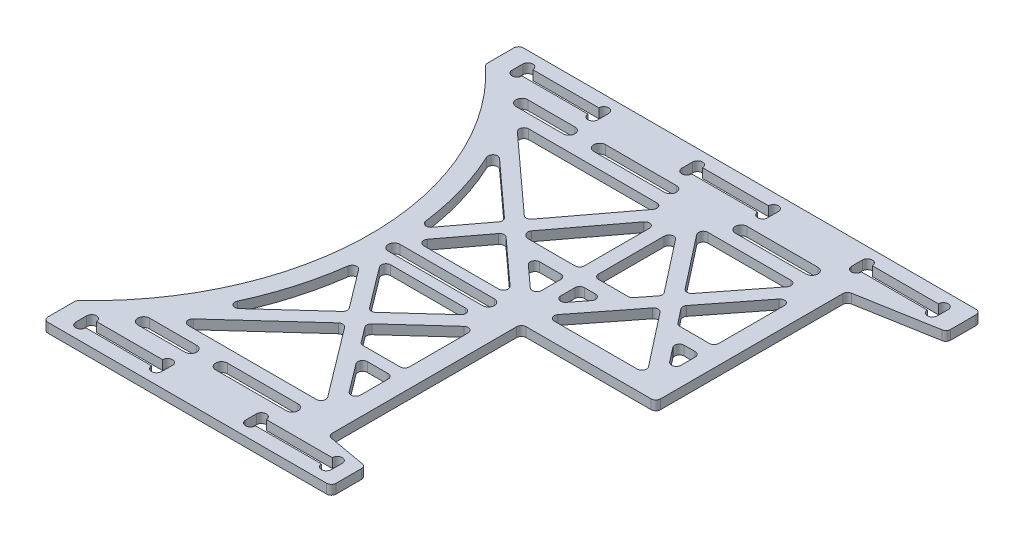
SolidWorks part; units mm, degrees
material "Thornel Mat VMA"
ref_plane "前视基准面" through (0, 0, 0) normal (0, 0, 1) x (1, 0, 0)
ref_plane "上视基准面" through (0, 0, 0) normal (0, 1, 0) x (1, 0, 0)
ref_plane "右视基准面" through (0, 0, 0) normal (1, 0, 0) x (0, 0, -1)
sketch "草图1" plane through (0, 0, 0) normal (0, 1, 0) x (1, 0, 0)
  line L0 (0, 0) -> (7.1511, 0) construction
  line L1 (-45.1, 47.4) -> (-26.9, 47.4)
  line L2 (-45.1, 47.4) -> (-45.1, 45.1)
  line L3 (-45.1, 45.1) -> (-26.9, 45.1)
  line L4 (-26.9, 47.4) -> (-26.9, 45.1)
  line L5 (-45.1, 47.4) -> (-26.9, 45.1) construction
  line L6 (-45.1, 45.1) -> (-26.9, 47.4) construction
  line L7 (9.1, 47.4) -> (-9.1, 47.4)
  line L8 (9.1, 47.4) -> (9.1, 45.1)
  line L9 (9.1, 45.1) -> (-9.1, 45.1)
  line L10 (-9.1, 47.4) -> (-9.1, 45.1)
  line L11 (9.1, 47.4) -> (-9.1, 45.1) construction
  line L12 (9.1, 45.1) -> (-9.1, 47.4) construction
  line L13 (45.1, 47.4) -> (26.9, 47.4)
  line L14 (45.1, 47.4) -> (45.1, 45.1)
  line L15 (45.1, 45.1) -> (26.9, 45.1)
  line L16 (26.9, 47.4) -> (26.9, 45.1)
  line L17 (45.1, 47.4) -> (26.9, 45.1) construction
  line L18 (45.1, 45.1) -> (26.9, 47.4) construction
  line L19 (0, 0) -> (0, 10.037) construction
  line L20 (45.1, -45.1) -> (26.9, -47.4) construction
  line L21 (49, -50.4) -> (-49, -50.4)
  line L22 (49, -50.4) -> (49, -43.1739)
  line L23 (49, 50.4) -> (-49, 50.4)
  line L24 (-49, -50.4) -> (-49, -43.3705)
  line L25 (49, -50.4) -> (-49, 50.4) construction
  line L26 (49, 50.4) -> (-49, -50.4) construction
  line L27 (45.1, -47.4) -> (26.9, -45.1) construction
  line L28 (9.1, -45.1) -> (-9.1, -47.4) construction
  line L29 (9.1, -47.4) -> (-9.1, -45.1) construction
  line L30 (-45.1, -45.1) -> (-26.9, -47.4) construction
  line L31 (-45.1, -47.4) -> (-26.9, -45.1) construction
  line L32 (26.9, -47.4) -> (26.9, -45.1)
  line L33 (45.1, -45.1) -> (26.9, -45.1)
  line L34 (45.1, -47.4) -> (45.1, -45.1)
  line L35 (45.1, -47.4) -> (26.9, -47.4)
  line L36 (-9.1, -47.4) -> (-9.1, -45.1)
  line L37 (9.1, -45.1) -> (-9.1, -45.1)
  line L38 (9.1, -47.4) -> (9.1, -45.1)
  line L39 (9.1, -47.4) -> (-9.1, -47.4)
  line L40 (-26.9, -47.4) -> (-26.9, -45.1)
  line L41 (-45.1, -45.1) -> (-26.9, -45.1)
  line L42 (-45.1, -47.4) -> (-45.1, -45.1)
  line L43 (-45.1, -47.4) -> (-26.9, -47.4)
  line L44 (-49, 43.3705) -> (-49, 50.4)
  line L45 (49, 43.1739) -> (31, 40)
  line L46 (31, 40) -> (31, -0.5)
  line L47 (31, -40) -> (49, -43.1739)
  line L48 (49, 43.1739) -> (49, 50.4)
  line L49 (-38, 40.1) -> (-28, 40.1) construction
  line L50 (-38, 41.35) -> (-28, 41.35)
  line L51 (-38, 38.85) -> (-28, 38.85)
  line L52 (-21.5, 40.1) -> (-6.5, 40.1) construction
  line L53 (-21.5, 41.35) -> (-6.5, 41.35)
  line L54 (-21.5, 38.85) -> (-6.5, 38.85)
  line L55 (8.5, 40.1) -> (23.5, 40.1) construction
  line L56 (8.5, 41.35) -> (23.5, 41.35)
  line L57 (8.5, 38.85) -> (23.5, 38.85)
  line L58 (31, -0.5) -> (2.5, -0.5)
  line L61 (-26.9, 46.25) -> (-9.1, 46.25) construction
  line L62 (-14, 46.25) -> (-14, 44.028) construction
  line L63 (-38, -40.1) -> (-28, -40.1) construction
  line L64 (-38, -41.35) -> (-28, -41.35)
  line L65 (-38, -38.85) -> (-28, -38.85)
  line L66 (-21.5, -40.1) -> (-6.5, -40.1) construction
  line L67 (-21.5, -41.35) -> (-6.5, -41.35)
  line L68 (-21.5, -38.85) -> (-6.5, -38.85)
  line L69 (2.5, -0.5) -> (2.5, -39.0048)
  line L72 (2.5, -39.0048) -> (31, -40)
  line L75 (-37.3687, 36.1) -> (-1.5, 36.1) construction
  line L76 (27, 36.1) -> (27, 3.5) construction
  line L77 (27, -36.1) -> (1.5, -36.1) construction
  line L78 (-26.0973, 3.5) -> (-1.5, 3.5) construction
  line L79 (-26.0973, -3.5) -> (-1.5, -3.5) construction
  line L80 (27, -3.5) -> (27, -36.1) construction
  line L81 (-1.5, 12.85) -> (-9.5573, 12.85)
  line L84 (1.5, 12.85) -> (6.9093, 12.85)
  line L87 (-1.5, 36.1) -> (-1.5, 3.5) construction
  line L88 (1.5, 36.1) -> (1.5, 3.5) construction
  line L89 (-25, 0) -> (-5, 0) construction
  line L90 (-25, 1.25) -> (-5, 1.25)
  line L91 (-25, -1.25) -> (-5, -1.25)
  line L92 (-12.8581, 15.85) -> (-1.5, 15.85)
  line L95 (9.2559, -23.75) -> (1.5, -23.75) construction
  line L98 (11.2114, -21.25) -> (1.5, -21.25) construction
  line L101 (-1.5, -3.5) -> (-1.5, -36.1) construction
  line L102 (1.5, -3.5) -> (27, -3.5) construction
  line L103 (1.5, -3.5) -> (1.5, -36.1) construction
  line L104 (1.5, 3.5) -> (27, 3.5) construction
  line L105 (-1.5, -36.1) -> (-37.3687, -36.1) construction
  line L106 (1.5, 36.1) -> (27, 36.1) construction
  line L107 (-26.0973, 3.5) -> (-1.5, 36.1) construction
  line L108 (-37.3687, 36.1) -> (-1.5, 3.5) construction
  line L109 (-35.1385, 36.1) -> (-16.2987, 18.977)
  line L110 (-34.3339, 31.3147) -> (-18.1131, 16.5722)
  line L111 (-26.2647, 5.7686) -> (-18.1131, 16.5722)
  line L112 (-24.2182, 3.5) -> (-15.8838, 14.546)
  line L113 (-35.1385, 36.1) -> (-3.3791, 36.1)
  line L114 (-1.5, 33.6096) -> (-1.5, 15.85)
  line L115 (-24.2182, 3.5) -> (-3.7302, 3.5)
  line L116 (-16.2987, 18.977) -> (-3.3791, 36.1)
  line L117 (-14.0693, 16.9508) -> (-12.8581, 15.85)
  line L118 (-14.0693, 16.9508) -> (-9.9102, 22.4631)
  line L119 (-15.8838, 14.546) -> (-3.7302, 3.5)
  line L120 (1.5, 5.9346) -> (6.9093, 12.85)
  line L121 (3.4044, 3.5) -> (14.25, 17.3654)
  line L122 (27, 36.1) -> (1.5, 3.5) construction
  line L123 (1.5, 36.1) -> (27, 3.5) construction
  line L124 (3.4044, 36.1) -> (14.25, 22.2346)
  line L125 (1.5, 33.6654) -> (8.2824, 24.9946)
  line L126 (3.4044, 36.1) -> (25.0956, 36.1)
  line L127 (27, 33.6654) -> (27, 15.85)
  line L128 (3.4044, 3.5) -> (25.0956, 3.5)
  line L129 (1.5, 5.9346) -> (1.5, 12.85)
  line L130 (14.25, 22.2346) -> (25.0956, 36.1)
  line L131 (16.1544, 19.8) -> (19.2441, 15.85)
  line L132 (16.1544, 19.8) -> (27, 33.6654)
  line L133 (14.25, 17.3654) -> (25.0956, 3.5)
  line L134 (3.4044, -3.5) -> (14.25, -17.3654) construction
  line L135 (14.25, -17.3654) -> (25.0956, -3.5) construction
  line L136 (3.4044, -3.5) -> (25.0956, -3.5) construction
  line L137 (16.1544, -19.8) -> (27, -33.6654) construction
  line L138 (16.1544, -19.8) -> (27, -5.9346) construction
  line L139 (27, -33.6654) -> (27, -5.9346) construction
  line L140 (3.4044, -36.1) -> (25.0956, -36.1) construction
  line L141 (14.25, -22.2346) -> (25.0956, -36.1) construction
  line L142 (3.4044, -36.1) -> (14.25, -22.2346) construction
  line L143 (1.5, -5.9346) -> (1.5, -21.25) construction
  line L144 (1.5, -5.9346) -> (12.3456, -19.8) construction
  line L145 (1.5, -33.6654) -> (9.2559, -23.75) construction
  line L147 (-14.0693, -16.9508) -> (-1.5, -5.527)
  line L148 (-1.5, -33.6096) -> (-1.5, -23.75)
  line L149 (-24.2182, -3.5) -> (-15.8838, -14.546)
  line L150 (-24.2182, -3.5) -> (-3.7302, -3.5)
  line L151 (-15.8838, -14.546) -> (-3.7302, -3.5)
  line L152 (-26.2647, -5.7686) -> (-18.1131, -16.5722)
  line L153 (-34.3339, -31.3147) -> (-18.1131, -16.5722)
  line L154 (-35.1385, -36.1) -> (-3.3791, -36.1)
  line L155 (-16.2987, -18.977) -> (-3.3791, -36.1)
  line L156 (-35.1385, -36.1) -> (-16.2987, -18.977)
  line L157 (-10.8255, -21.25) -> (-1.5, -21.25)
  line L160 (-8.9392, -23.75) -> (-1.5, -23.75)
  line L163 (14.25, -17.3654) -> (14.25, -10.4038) construction
  line L164 (-8.9392, -23.75) -> (-1.5, -33.6096)
  line L165 (11.2114, -21.25) -> (12.3456, -19.8) construction
  line L169 (1.5, -23.75) -> (1.5, -33.6654) construction
  line L170 (1.5, 15.85) -> (9.2559, 15.85)
  line L175 (-1.5, -21.25) -> (-1.5, -5.527)
  line L176 (-14.0693, -16.9508) -> (-10.8255, -21.25)
  line L178 (-1.5, 12.85) -> (-1.5, 5.527)
  line L181 (31, -31.8857) -> (31, -40) construction
  line L182 (9.2559, 15.85) -> (12.3456, 19.8)
  line L188 (-9.9102, 22.4631) -> (-1.5, 33.6096)
  line L189 (1.5, 15.85) -> (1.5, 33.6654)
  line L190 (8.2824, 24.9946) -> (12.3456, 19.8)
  line L191 (-9.5573, 12.85) -> (-1.5, 5.527)
  line L192 (19.2441, 15.85) -> (27, 15.85)
  line L193 (21.5907, 12.85) -> (27, 12.85)
  line L194 (21.5907, 12.85) -> (27, 5.9346)
  line L195 (27, 12.85) -> (27, 5.9346)
  line L196 (12.1, -39.34) -> (12.1, -50.4)
  line L197 (2.5, -39.0048) -> (2.5, -41.4811)
  line L198 (2.5, -41.4811) -> (12.1, -43.1739)
  circle A0 centre (-8.05, 47.4) radius 1.05
  circle A1 centre (8.05, 47.4) radius 1.05
  circle A2 centre (8.05, 45.1) radius 1.05
  circle A3 centre (-8.05, 45.1) radius 1.05
  circle A4 centre (-44.05, 47.4) radius 1.05
  circle A5 centre (-44.05, 45.1) radius 1.05
  circle A6 centre (-27.95, 47.4) radius 1.05
  circle A7 centre (-27.95, 45.1) radius 1.05
  circle A8 centre (27.95, 45.1) radius 1.05
  circle A9 centre (44.05, 45.1) radius 1.05
  circle A10 centre (44.05, 47.4) radius 1.05
  circle A11 centre (27.95, 47.4) radius 1.05
  circle A12 centre (27.95, -47.4) radius 1.05
  circle A13 centre (44.05, -47.4) radius 1.05
  circle A14 centre (44.05, -45.1) radius 1.05
  circle A15 centre (27.95, -45.1) radius 1.05
  circle A16 centre (-27.95, -45.1) radius 1.05
  circle A17 centre (-27.95, -47.4) radius 1.05
  circle A18 centre (-44.05, -45.1) radius 1.05
  circle A19 centre (-44.05, -47.4) radius 1.05
  circle A20 centre (-8.05, -45.1) radius 1.05
  circle A21 centre (8.05, -45.1) radius 1.05
  circle A22 centre (8.05, -47.4) radius 1.05
  circle A23 centre (-8.05, -47.4) radius 1.05
  arc A24 (-49, -43.3705) -> (-49, 43.3705) centre (-89, 0) ccw
  arc A25 (-38, 41.35) -> (-38, 38.85) centre (-38, 40.1) ccw
  arc A26 (-28, 38.85) -> (-28, 41.35) centre (-28, 40.1) ccw
  arc A27 (-21.5, 41.35) -> (-21.5, 38.85) centre (-21.5, 40.1) ccw
  arc A28 (-6.5, 38.85) -> (-6.5, 41.35) centre (-6.5, 40.1) ccw
  arc A29 (8.5, 41.35) -> (8.5, 38.85) centre (8.5, 40.1) ccw
  arc A30 (23.5, 38.85) -> (23.5, 41.35) centre (23.5, 40.1) ccw
  arc A33 (-38, -41.35) -> (-38, -38.85) centre (-38, -40.1) cw
  arc A34 (-28, -38.85) -> (-28, -41.35) centre (-28, -40.1) cw
  arc A35 (-21.5, -41.35) -> (-21.5, -38.85) centre (-21.5, -40.1) cw
  arc A36 (-6.5, -38.85) -> (-6.5, -41.35) centre (-6.5, -40.1) cw
  arc A41 (-37.3687, 36.1) -> (-26.0973, 3.5) centre (-89, 0) cw construction
  arc A42 (-26.0973, -3.5) -> (-37.3687, -36.1) centre (-89, 0) cw construction
  arc A47 (-25, 1.25) -> (-25, -1.25) centre (-25, 0) ccw
  arc A48 (-5, -1.25) -> (-5, 1.25) centre (-5, 0) ccw
  arc A55 (-34.3339, 31.3147) -> (-26.2647, 5.7686) centre (-89, 0) cw
  arc A56 (-34.3339, -31.3147) -> (-26.2647, -5.7686) centre (-89, 0) ccw
  point P0 (-36, 46.25)
  point P5 (0, 46.25)
  point P10 (36, 46.25)
  point P43 (0, 0)
  point P86 (36, -46.25)
  point P87 (0, -46.25)
  point P88 (-36, -46.25)
  point P96 (-33, 40.1)
  point P101 (-14, 40.1)
  point P108 (16, 40.1)
  point P128 (-33, -40.1)
  point P135 (-14, -40.1)
  point P182 (-15, 0)
  dimension "D4" = 2.1
  dimension "D5" = 2.1
  dimension "D11" = 118
  dimension "D15" = 1.25
  dimension "D16" = 1.25
  dimension "D17" = 26
  dimension "D25" = 4
  dimension "D29" = 2
  dimension "D43" = 2.5
  dimension "D55" = 1.25
  dimension "D1" = 2.3
  dimension "D2" = 36
  dimension "D3" = 18.2
  dimension "D6" = 3
  dimension "D7" = 13
  dimension "D8" = 98
  dimension "D9" = 92.5
  dimension "D10" = 40
  dimension "D12" = 18
  dimension "D13" = 80
  dimension "D14" = 80
  dimension "D18" = 5
  dimension "D19" = 15
  dimension "D20" = 30
  dimension "D21" = 4
  dimension "D22" = 4
  dimension "D23" = 16
  dimension "D24" = 10
  dimension "D26" = 4
  dimension "D27" = 7
  dimension "D28" = 4
  dimension "D30" = 3
  dimension "D31" = 3
  dimension "D36" = 15
  dimension "D40" = 1.5
  dimension "D41" = 3
  dimension "D42" = 3
  dimension "D44" = 3
  dimension "D45" = 20
  dimension "D54" = 20
  dimension "D56" = 14
extrude "凸台-拉伸1" add sketch "草图1" along normal blind 2 contours A24 L24 L21 L22 L23 A15 L33 A14 L34 A13 L35 A12 L32 A7 L3 A5 L2 A4 L1 A6 L4 A3 L10 A0 L7 A1 L8 A2 L9 L16 A11 L13 A10 L14 A9 L15 A8 L43 A19 L42 A18 L41 A16 L40 A17
fillet "圆角1" radius 1 64 edges at (-26.2647, 1, -5.7686) (-18.1131, 1, -16.5722) (31, 1, -40) (-3.7302, 1, 3.5) (-24.2182, 1, 3.5) (-15.8838, 1, 14.546) (25.0956, 1, -36.1) (3.4044, 1, -36.1) (14.25, 1, -22.2346) (-3.3791, 1, -36.1) (-16.2987, 1, -18.977) (-1.5, 1, -33.6096) (-14.0693, 1, -16.9508) (-24.2182, 1, -3.5) (-3.7302, 1, -3.5) (-15.8838, 1, -14.546) (1.5, 1, -5.9346) (27, 1, -33.6654) (16.1544, 1, -19.8) (3.4044, 1, -3.5) (25.0956, 1, -3.5) (14.25, 1, -17.3654) (-3.3791, 1, 36.1) (-16.2987, 1, 18.977) (-35.1385, 1, 36.1) (-18.1131, 1, 16.5722) (-26.2647, 1, 5.7686) (-34.3339, 1, 31.3147) (-34.3339, 1, -31.3147) (-35.1385, 1, -36.1) (-1.5, 1, 5.527) (-10.8255, 1, 21.25) (-1.5, 1, 21.25) (-14.0693, 1, 16.9508) (-1.5, 1, 33.6096) (-1.5, 1, 23.75) (-8.9392, 1, 23.75) (1.5, 1, -33.6654) (-49, 1, 50.4) (-49, 1, 43.3705) (-49, 1, -43.3705) (-49, 1, -50.4) (49, 1, -50.4) (49, 1, -43.1739) (2.5, 1, 0.5) (27, 1, -15.85) (19.2441, 1, -15.85) (-1.5, 1, -5.527) (-1.5, 1, -12.85) (-9.5573, 1, -12.85) (6.9093, 1, -12.85) (1.5, 1, -12.85) (-12.8581, 1, -15.85) (-1.5, 1, -15.85) (1.5, 1, -15.85) (9.2559, 1, -15.85) (12.3456, 1, -19.8) (21.5907, 1, -12.85) (27, 1, -5.9346) (27, 1, -12.85) (31, 1, 0.5) (12.1, 1, 43.1739) (12.1, 1, 50.4) (2.5, 1, 41.4811)
